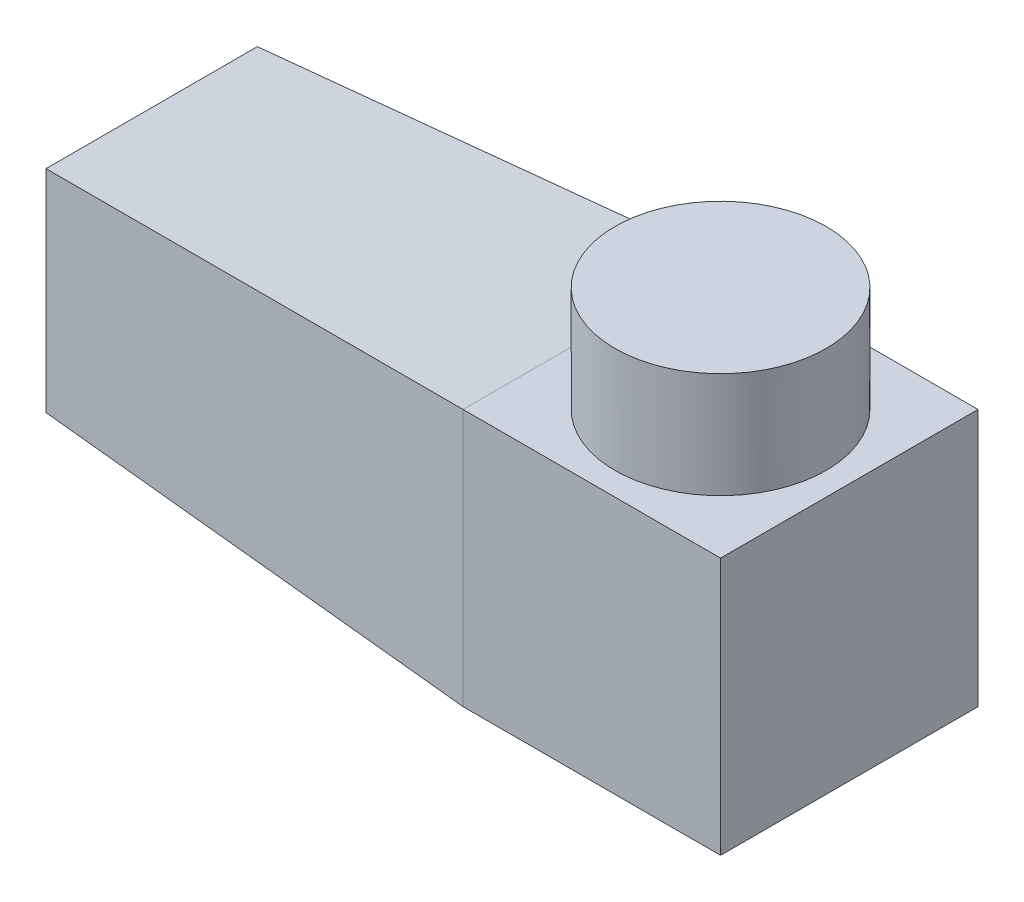
SolidWorks part; units mm, degrees
ref_plane "Front Plane" through (0, 0, 0) normal (0, 0, 1) x (1, 0, 0)
ref_plane "Top Plane" through (0, 0, 0) normal (0, 1, 0) x (1, 0, 0)
ref_plane "Right Plane" through (0, 0, 0) normal (1, 0, 0) x (0, 0, -1)
sketch "Sketch1" plane through (0, 0, 0) normal (1, 0, 0) x (0, 0, -1)
  line L1 (-60, 60) -> (60, 60)
  line L2 (-60, 60) -> (-60, -60)
  line L3 (-60, -60) -> (60, -60)
  line L4 (60, 60) -> (60, -60)
  point P4 (0, -60)
  point P5 (-60, 0)
  dimension "D1" = 120
  dimension "D2" = 120
extrude "Boss-Extrude1" add sketch "Sketch1" along normal blind 250 draft 3 draft outward yes
sketch "Sketch2" plane through (250, 0, 0) normal (1, 0, 0) x (0, 0, -1)
  line L0 (-73.1019, 73.1019) -> (-73.1019, -73.1019) construction
  line L1 (73.1019, 73.1019) -> (-73.1019, 73.1019) construction
  line L2 (73.1019, -73.1019) -> (73.1019, 73.1019) construction
  line L3 (-73.1019, -73.1019) -> (73.1019, -73.1019) construction
  line L4 (-73.1019, 73.1019) -> (-73.1019, -73.1019)
  line L5 (73.1019, 73.1019) -> (-73.1019, 73.1019)
  line L6 (73.1019, -73.1019) -> (73.1019, 73.1019)
  line L7 (-73.1019, -73.1019) -> (73.1019, -73.1019)
extrude "Boss-Extrude2" add sketch "Sketch2" along normal blind 146.2
sketch "Sketch3" plane through (0, 73.1019, 0) normal (0, 1, 0) x (1, 0, 0)
  line L0 (396.2, 73.1019) -> (250, 73.1019) construction
  circle A0 centre (323.1, 0) radius 60
  point P0 (323.1, 73.1019)
  dimension "D1" = 120
extrude "Boss-Extrude3" add sketch "Sketch3" along normal blind 60
